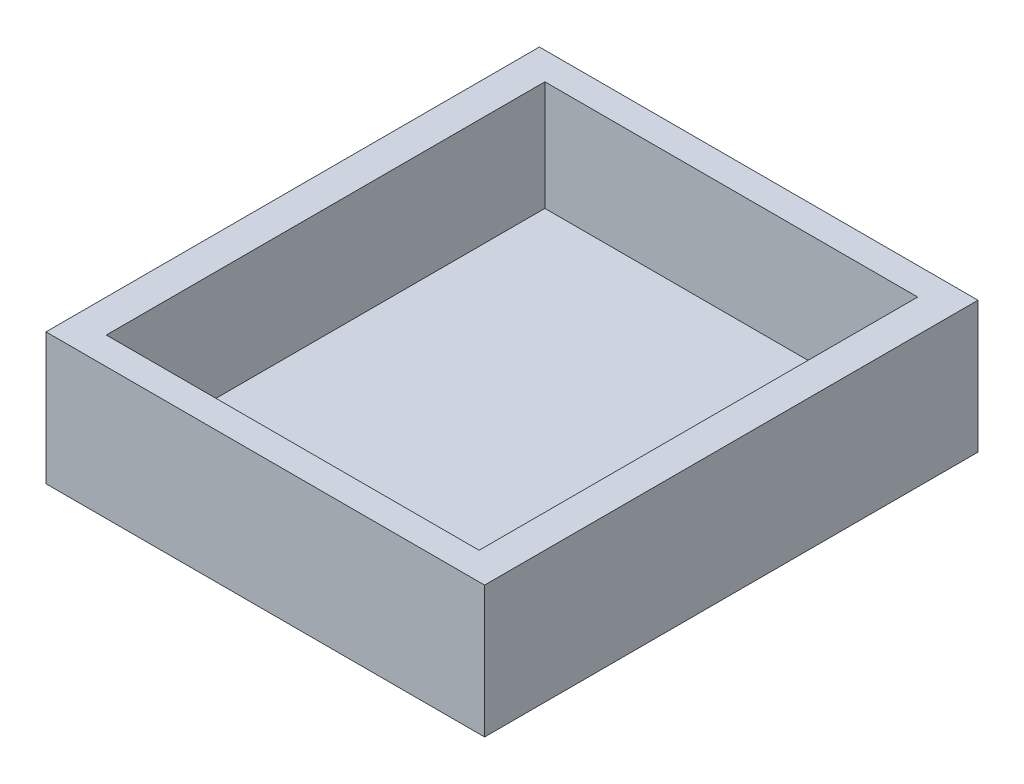
SolidWorks part; units mm, degrees
ref_plane "Front Plane" through (0, 0, 0) normal (0, 0, 1) x (1, 0, 0)
ref_plane "Top Plane" through (0, 0, 0) normal (0, 1, 0) x (1, 0, 0)
ref_plane "Right Plane" through (0, 0, 0) normal (1, 0, 0) x (0, 0, -1)
sketch "Sketch1" plane through (0, 0, 0) normal (0, 1, 0) x (1, 0, 0)
  line L1 (0, 0) -> (40, 0)
  line L2 (0, 0) -> (0, 45)
  line L3 (0, 45) -> (40, 45)
  line L4 (40, 0) -> (40, 45)
  dimension "D1" = 45
  dimension "D2" = 40
extrude "Boss-Extrude1" add sketch "Sketch1" along normal blind 12
sketch "Sketch2" plane through (0, 12, 0) normal (0, 1, 0) x (1, 0, 0)
  line L1 (3, 42.5) -> (37, 42.5)
  line L2 (3, 42.5) -> (3, 2.5)
  line L3 (3, 2.5) -> (37, 2.5)
  line L4 (37, 42.5) -> (37, 2.5)
  line L5 (0, 45) -> (0, 0) construction
  line L7 (0, 0) -> (40, 0) construction
  dimension "D1" = 40
  dimension "D2" = 34
  dimension "D3" = 2.5
  dimension "D4" = 3
extrude "Cut-Extrude1" cut sketch "Sketch2" against normal blind 10
